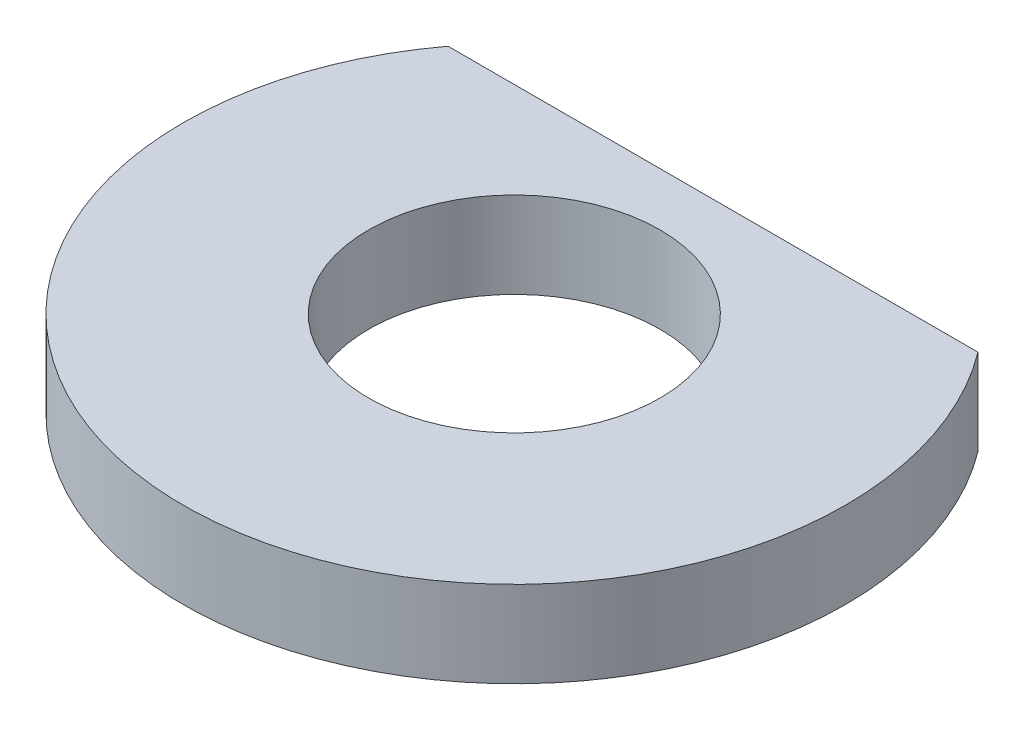
SolidWorks part; units mm, degrees
material "AISI 1020"
ref_plane "Front Plane" through (0, 0, 0) normal (0, 0, 1) x (1, 0, 0)
ref_plane "Top Plane" through (0, 0, 0) normal (0, 1, 0) x (1, 0, 0)
ref_plane "Right Plane" through (0, 0, 0) normal (1, 0, 0) x (0, 0, -1)
sketch "Sketch1" plane through (0, 0, 0) normal (0, 1, 0) x (1, 0, 0)
  circle A0 centre (0, 0) radius 6.35
  circle A1 centre (0, 0) radius 2.794
  dimension "D1" = 12.7
  dimension "D2" = 5.588
extrude "Boss-Extrude1" add sketch "Sketch1" along normal blind 1.651
sketch "Sketch2" plane through (0, 1.651, 0) normal (0, 1, 0) x (1, 0, 0)
  line L0 (-5.08, 3.81) -> (5.08, 3.81)
  circle A0 centre (0, 0) radius 6.35 construction
  circle A1 centre (0, 0) radius 2.794 construction
  dimension "D1" = 3.81
extrude "Cut-Extrude1" cut sketch "Sketch2" against normal through all and the other way through all
